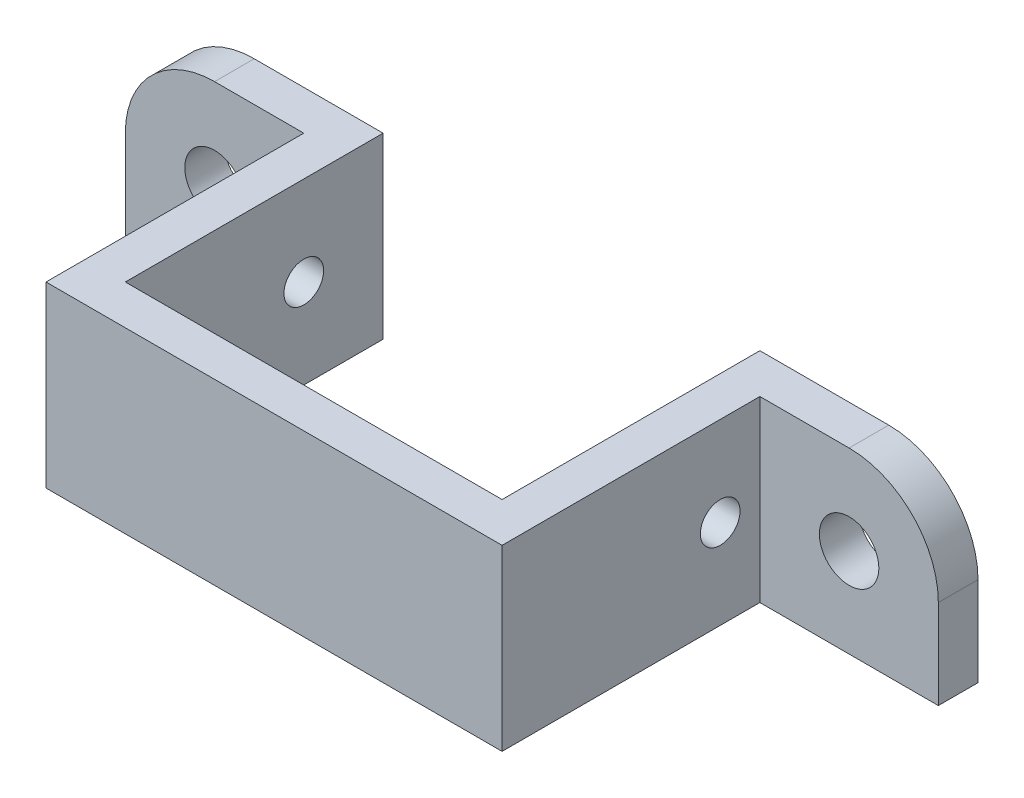
SolidWorks part; units mm, degrees
ref_plane "Front Plane" through (0, 0, 0) normal (0, 0, 1) x (1, 0, 0)
ref_plane "Top Plane" through (0, 0, 0) normal (0, 1, 0) x (1, 0, 0)
ref_plane "Right Plane" through (0, 0, 0) normal (1, 0, 0) x (0, 0, -1)
sketch "Sketch1" plane through (0, 0, 0) normal (0, 1, 0) x (1, 0, 0)
  line L0 (-20.5, 13) -> (-9.5, 13)
  line L1 (-9.5, 13) -> (-9.5, 0)
  line L2 (-9.5, 0) -> (9.5, 0)
  line L3 (9.5, 0) -> (9.5, 13)
  line L4 (9.5, 13) -> (20.5, 13)
  line L5 (20.5, 13) -> (20.5, 11)
  line L6 (20.5, 11) -> (11.5, 11)
  line L7 (11.5, 11) -> (11.5, -2)
  line L8 (11.5, -2) -> (-11.5, -2)
  line L9 (-11.5, -2) -> (-11.5, 11)
  line L10 (-11.5, 11) -> (-20.5, 11)
  line L11 (-20.5, 11) -> (-20.5, 13)
  point P2 (0, 0)
  dimension "D1" = 19
  dimension "D2" = 2
  dimension "D3" = 15
  dimension "D4" = 2
  dimension "D5" = 2
  dimension "D6" = 2
  dimension "D7" = 11
extrude "Boss-Extrude1" add sketch "Sketch1" along normal blind 9
sketch "Sketch2" plane through (-11.5, 0, 0) normal (-1, 0, 0) x (0, 0, 1)
  line L0 (-11, 9) -> (-11, 0) construction
  line L1 (-11, 9) -> (-11, 0) construction
  line L2 (-11, 4.5) -> (-9, 4.5) construction
  circle A0 centre (-9, 4.5) radius 1
  dimension "D2" = 2
  dimension "D1" = 2
extrude "Cut-Extrude1" cut sketch "Sketch2" against normal through all
sketch "Sketch3" plane through (0, 0, -11) normal (0, 0, 1) x (1, 0, 0)
  line L0 (0, 0) -> (0, 9) construction
  line L1 (-11.5, 9) -> (11.5, 9) construction
  line L2 (-11.5, 4.5) -> (-16, 4.5) construction
  line L3 (11.5, 0) -> (11.5, 9) construction
  line L4 (-20.5, 0) -> (-11.5, 0)
  line L5 (-11.5, 0) -> (-11.5, 9)
  line L6 (-11.5, 9) -> (-20.5, 9)
  line L7 (-20.5, 9) -> (-20.5, 0)
  line L8 (-20.5, 0) -> (-11.5, 0)
  line L9 (-11.5, 0) -> (-11.5, 9) construction
  line L10 (-11.5, 9) -> (-20.5, 9)
  line L11 (-20.5, 9) -> (-20.5, 0)
  line L12 (11.5, 4.5) -> (16, 4.5) construction
  line L13 (20.5, 9) -> (20.5, 0)
  line L14 (11.5, 9) -> (20.5, 9)
  line L15 (20.5, 0) -> (11.5, 0)
  circle A0 centre (-16, 4.5) radius 1.5
  arc A1 (-16, 9) -> (-16, 0) centre (-16, 4.5) ccw
  arc A2 (16, 9) -> (16, 0) centre (16, 4.5) cw
  circle A3 centre (16, 4.5) radius 1.5
  line M9 (-20.5, 9) -> (-20.5, 0)
  dimension "D2" = 3
  dimension "D3" = 4.5
  dimension "D1" = 0
extrude "Cut-Extrude2" cut sketch "Sketch3" against normal through all contours A0 | A1 L10 M9 | L14 A2 L13 | A3
